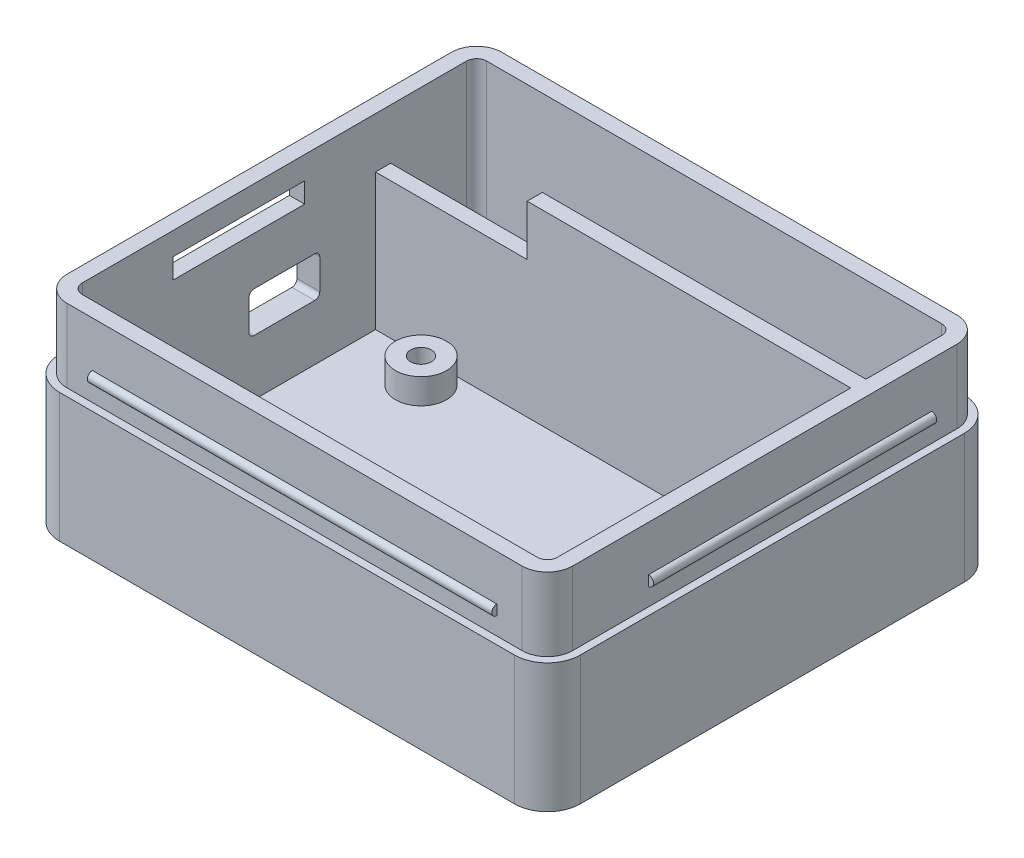
SolidWorks part; units mm, degrees
ref_plane "Plan de face" through (0, 0, 0) normal (0, 0, 1) x (1, 0, 0)
ref_plane "Plan de dessus" through (0, 0, 0) normal (0, 1, 0) x (1, 0, 0)
ref_plane "Plan de droite" through (0, 0, 0) normal (1, 0, 0) x (0, 0, -1)
sketch "Esquisse1" plane through (0, 0, 0) normal (0, 1, 0) x (1, 0, 0)
  line L1 (-50, -33) -> (50, -33)
  line L2 (-50, -33) -> (-50, 33)
  line L3 (-50, 33) -> (50, 33)
  line L4 (50, -33) -> (50, 33)
  line L5 (-50, -33) -> (50, 33) construction
  line L6 (-50, 33) -> (50, -33) construction
  point P0 (0, 0)
  dimension "D1" = 100
  dimension "D2" = 66
extrude "Boss.-Extru.1" add sketch "Esquisse1" along normal blind 40
shell "Coque1" thickness 3
sketch "Esquisse2" plane through (0, 0, 0) normal (0, -1, 0) x (1, 0, 0)
  line L0 (-50, -33) -> (-50, -53)
  line L1 (-50, -53) -> (50, -53)
  line L2 (50, -53) -> (50, -33)
  line L3 (47, -33) -> (47, -50)
  line L4 (50, -33) -> (-50, -33) construction
  line L5 (47, -50) -> (-47, -50)
  line L6 (-47, -50) -> (-47, -33)
  line L7 (47, 30) -> (47, -30) construction
  line L8 (-47, -30) -> (-47, 30) construction
  line L9 (50, -33) -> (47, -33)
  line L10 (-47, -33) -> (-50, -33)
  line L11 (50, -33) -> (-50, -33) construction
  dimension "D1" = 3
  dimension "D2" = 20
extrude "Boss.-Extru.2" add sketch "Esquisse2" against normal up to surface (40 mm away) up to face at (0, 40, 0)
sketch "Esquisse3" plane through (0, 0, 0) normal (0, -1, 0) x (1, 0, 0)
  line L0 (47, -33) -> (47, -50) construction
  line L1 (47, -50) -> (-47, -50) construction
  line L2 (-47, -50) -> (-47, -33) construction
  line L3 (47, -33) -> (-47, -33) construction
  line L4 (47, -33) -> (47, -50)
  line L5 (47, -50) -> (-47, -50)
  line L6 (-47, -50) -> (-47, -33)
  line L7 (47, -33) -> (-47, -33)
extrude "Boss.-Extru.3" add sketch "Esquisse3" against normal up to surface (3 mm away) up to face at (0, 3, 0)
fillet "Congé1" radius 2 4 edges at (47, 21.5, 30) (-47, 21.5, 30) (47, 21.5, -50) (-47, 21.5, -50)
fillet "Congé2" radius 5 4 edges at (-50, 20, -53) (50, 20, -53) (-50, 20, 33) (50, 20, 33)
sketch "Esquisse4" plane through (50, 0, 0) normal (1, 0, 0) x (0, 0, -1)
  line L0 (-35.6696, 30) -> (53.7991, 30) construction
  line L1 (-28, 40) -> (48, 40) construction
  line L2 (-33, 0) -> (-33, 40) construction
  line L3 (-33, 31) -> (-33, 29)
  arc A0 (-33, 31) -> (-33, 29) centre (-33, 30) ccw
  dimension "D2" = 1
  dimension "D1" = 10
extrude "Boss.-Extru.4" add sketch "Esquisse4" against normal blind 80 from offset 10 offset against normal yes
ref_plane "Plan1" through (0, 0, -10) normal (0, 0, -1) x (-1, 0, 0)
mirror "Symétrie1" about plane through (0, 0, -10) normal (0, 0, -1) of "Boss.-Extru.4"
sketch "Esquisse5" plane through (0, 0, -53) normal (0, 0, -1) x (-1, 0, 0)
  line L0 (41.1298, 30) -> (54.9121, 30) construction
  line L1 (-45, 40) -> (45, 40) construction
  line L2 (50, 40) -> (50, 0) construction
  line L3 (50, 31) -> (50, 29)
  arc A0 (50, 29) -> (50, 31) centre (50, 30) ccw
  dimension "D2" = 1
  dimension "D1" = 10
extrude "Boss.-Extru.5" add sketch "Esquisse5" against normal blind 56 from offset 10 offset against normal yes
mirror "Symétrie2" about plane through (0, 0, 0) normal (1, 0, 0) of "Boss.-Extru.5"
sketch "Esquisse6" plane through (0, 0, -30) normal (0, 0, 1) x (1, 0, 0)
  line L1 (-47, 40) -> (-17, 40)
  line L2 (-47, 40) -> (-47, 30)
  line L3 (-47, 30) -> (-17, 30)
  line L4 (-17, 40) -> (-17, 30)
  dimension "D1" = 30
  dimension "D2" = 10
extrude "Enlèv. mat.-Extru.1" cut sketch "Esquisse6" against normal blind 5
sketch "Esquisse7" plane through (0, 3, 0) normal (0, 1, 0) x (1, 0, 0)
  line L0 (-33, 30) -> (-33, -24) construction
  line L1 (39, 30) -> (39, -30) construction
  line L2 (47, -28) -> (47, 30) construction
  line L3 (47, 30) -> (-47, 30) construction
  line L4 (-45, -30) -> (45, -30) construction
  line L5 (47, 30) -> (-17, 30) construction
  circle A0 centre (-33, 25) radius 5.05
  circle A1 centre (-33, -24) radius 5
  circle A2 centre (39, -18) radius 5
  circle A3 centre (39, 10) radius 5
  dimension "D4" = 10.1
  dimension "D5" = 10
  dimension "D8" = 10
  dimension "D9" = 10
  dimension "D1" = 72
  dimension "D2" = 8
  dimension "D3" = 49
  dimension "D6" = 5
  dimension "D7" = 6
  dimension "D10" = 28
extrude "Boss.-Extru.6" add sketch "Esquisse7" along normal blind 5
sketch "Esquisse8" plane through (0, 8, 0) normal (0, 1, 0) x (1, 0, 0)
  circle A0 centre (-33, 25) radius 2.05
  circle A1 centre (-33, -24) radius 2.05
  circle A2 centre (39, 10) radius 2.05
  circle A3 centre (39, -18) radius 2.05
  dimension "D1" = 4.1
  dimension "D2" = 4.1
  dimension "D3" = 4.1
  dimension "D4" = 4.1
extrude "Enlèv. mat.-Extru.2" cut sketch "Esquisse8" against normal through all
sketch "Esquisse9" plane through (0, 0, 0) normal (0, -1, 0) x (1, 0, 0)
  line L1 (-29.6514, 24) -> (-31.3257, 26.9)
  line L2 (-31.3257, 26.9) -> (-34.6743, 26.9)
  line L3 (-34.6743, 26.9) -> (-36.3486, 24)
  line L4 (-36.3486, 24) -> (-34.6743, 21.1)
  line L5 (-34.6743, 21.1) -> (-31.3257, 21.1)
  line L6 (-31.3257, 21.1) -> (-29.6514, 24)
  line L7 (42.3486, 18) -> (40.6743, 20.9)
  line L8 (40.6743, 20.9) -> (37.3257, 20.9)
  line L9 (37.3257, 20.9) -> (35.6514, 18)
  line L10 (35.6514, 18) -> (37.3257, 15.1)
  line L11 (37.3257, 15.1) -> (40.6743, 15.1)
  line L12 (40.6743, 15.1) -> (42.3486, 18)
  line L13 (42.3486, -10) -> (40.6743, -7.1)
  line L14 (40.6743, -7.1) -> (37.3257, -7.1)
  line L15 (37.3257, -7.1) -> (35.6514, -10)
  line L16 (35.6514, -10) -> (37.3257, -12.9)
  line L17 (37.3257, -12.9) -> (40.6743, -12.9)
  line L18 (40.6743, -12.9) -> (42.3486, -10)
  line L19 (-29.6514, -25) -> (-31.3257, -22.1)
  line L20 (-31.3257, -22.1) -> (-34.6743, -22.1)
  line L21 (-34.6743, -22.1) -> (-36.3486, -25)
  line L22 (-36.3486, -25) -> (-34.6743, -27.9)
  line L23 (-34.6743, -27.9) -> (-31.3257, -27.9)
  line L24 (-31.3257, -27.9) -> (-29.6514, -25)
  circle A0 centre (-33, 24) radius 2.9 construction
  circle A1 centre (39, 18) radius 2.9 construction
  circle A2 centre (39, -10) radius 2.9 construction
  circle A3 centre (-33, -25) radius 2.9 construction
  dimension "D3" = 5.8
  dimension "D4" = 5.8
  dimension "D1" = 5.8
  dimension "D2" = 5.8
extrude "Enlèv. mat.-Extru.3" [suppressed] cut sketch "Esquisse9" against normal blind 2.5
sketch "Esquisse10" plane through (0, 0, 0) normal (0, -1, 0) x (1, 0, 0)
  line L4 (50, 28) -> (50, -48) construction
  line L5 (-45, -53) -> (45, -53) construction
  line L6 (-50, -48) -> (-50, 28) construction
  line L7 (-45, 33) -> (45, 33) construction
  line L8 (-51.5, 28) -> (-51.5, -48)
  line L9 (-45, -54.5) -> (45, -54.5)
  line L10 (51.5, -48) -> (51.5, 28)
  line L11 (45, 34.5) -> (-45, 34.5)
  line L12 (-51.5, 28) -> (-51.5, -48)
  line L13 (-45, -54.5) -> (45, -54.5)
  line L14 (51.5, -48) -> (51.5, 28)
  line L15 (45, 34.5) -> (-45, 34.5)
  line L16 (50, 28) -> (50, -48)
  line L17 (-45, -53) -> (45, -53)
  line L18 (-50, -48) -> (-50, 28)
  line L19 (-45, 33) -> (45, 33)
  arc A4 (50, 28) -> (45, 33) centre (45, 28) ccw construction
  arc A5 (45, -53) -> (50, -48) centre (45, -48) ccw construction
  arc A6 (-50, -48) -> (-45, -53) centre (-45, -48) ccw construction
  arc A7 (-45, 33) -> (-50, 28) centre (-45, 28) ccw construction
  arc A8 (-51.5, -48) -> (-45, -54.5) centre (-45, -48) ccw
  arc A9 (45, -54.5) -> (51.5, -48) centre (45, -48) ccw
  arc A10 (51.5, 28) -> (45, 34.5) centre (45, 28) ccw
  arc A11 (-45, 34.5) -> (-51.5, 28) centre (-45, 28) ccw
  arc A12 (-51.5, -48) -> (-45, -54.5) centre (-45, -48) ccw
  arc A13 (45, -54.5) -> (51.5, -48) centre (45, -48) ccw
  arc A14 (51.5, 28) -> (45, 34.5) centre (45, 28) ccw
  arc A15 (-45, 34.5) -> (-51.5, 28) centre (-45, 28) ccw
  arc A16 (50, 28) -> (45, 33) centre (45, 28) ccw
  arc A17 (45, -53) -> (50, -48) centre (45, -48) ccw
  arc A18 (-50, -48) -> (-45, -53) centre (-45, -48) ccw
  arc A19 (-45, 33) -> (-50, 28) centre (-45, 28) ccw
  dimension "D1" = 1.5
extrude "Boss.-Extru.7" add sketch "Esquisse10" against normal blind 25.5
sketch "Esquisse11" plane through (-47, 0, 0) normal (1, 0, 0) x (0, 0, -1)
  line L0 (30, 8) -> (19.95, 8) construction
  line L1 (4.975, 14) -> (18.975, 14)
  line L2 (4.975, 14) -> (4.975, 22)
  line L3 (4.975, 22) -> (18.975, 22)
  line L4 (18.975, 14) -> (18.975, 22)
  line L5 (4.975, 14) -> (18.975, 22) construction
  line L6 (4.975, 22) -> (18.975, 14) construction
  line L7 (24.975, 8) -> (24.975, 18) construction
  point P0 (11.975, 18)
  dimension "D1" = 8
  dimension "D2" = 14
  dimension "D3" = 13
  dimension "D4" = 6
extrude "Enlèv. mat.-Extru.4" cut sketch "Esquisse11" against normal blind 10
fillet "Congé3" radius 1 4 edges at (-49.25, 14, -4.975) (-49.25, 14, -18.975) (-49.25, 22, -4.975) (-49.25, 22, -18.975)
sketch "Esquisse12" plane through (-47, 0, 0) normal (1, 0, 0) x (0, 0, -1)
  line L0 (30, 8) -> (19.95, 8) construction
  line L1 (-10.025, 35.5) -> (15.975, 35.5)
  line L2 (-10.025, 35.5) -> (-10.025, 31.5)
  line L3 (-10.025, 31.5) -> (15.975, 31.5)
  line L4 (15.975, 35.5) -> (15.975, 31.5)
  line L5 (-10.025, 35.5) -> (15.975, 31.5) construction
  line L6 (-10.025, 31.5) -> (15.975, 35.5) construction
  point P0 (2.975, 33.5)
  point P9 (24.975, 8)
  dimension "D1" = 23.5
  dimension "D2" = 9
  dimension "D3" = 26
  dimension "D4" = 4
extrude "Enlèv. mat.-Extru.5" cut sketch "Esquisse12" against normal blind 10
